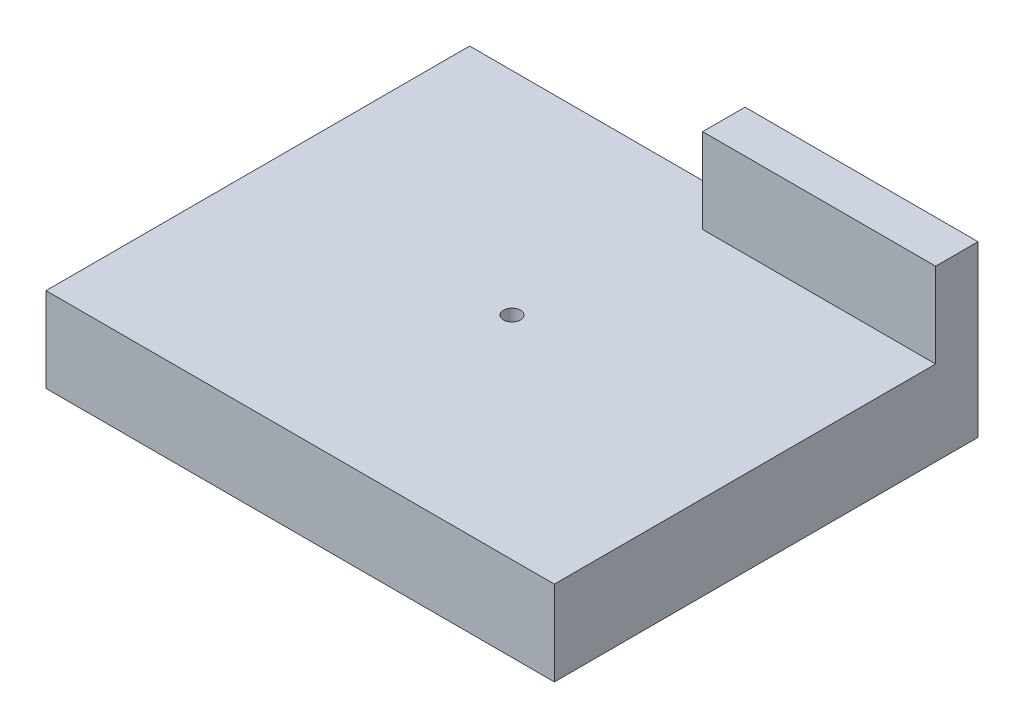
SolidWorks part; units mm, degrees
ref_plane "Front Plane" through (0, 0, 0) normal (0, 0, 1) x (1, 0, 0)
ref_plane "Top Plane" through (0, 0, 0) normal (0, 1, 0) x (1, 0, 0)
ref_plane "Right Plane" through (0, 0, 0) normal (1, 0, 0) x (0, 0, -1)
sketch "Sketch1" plane through (0, 0, 0) normal (0, 1, 0) x (1, 0, 0)
  line L1 (-30, -25) -> (30, -25)
  line L2 (-30, -25) -> (-30, 25)
  line L3 (-30, 25) -> (30, 25)
  line L4 (30, -25) -> (30, 25)
  line L5 (-30, -25) -> (30, 25) construction
  line L6 (-30, 25) -> (30, -25) construction
  point P0 (0, 0)
  dimension "D1" = 50
  dimension "D2" = 60
extrude "Boss-Extrude1" add sketch "Sketch1" along normal blind 20
sketch "Sketch2" plane through (0, 20, 0) normal (0, 1, 0) x (1, 0, 0)
  line L0 (-30, -25) -> (30, -25) construction
  line L1 (-30, 25) -> (2.5, 25)
  line L2 (-30, 25) -> (-30, -25)
  line L3 (-30, -25) -> (2.5, -25)
  line L4 (2.5, 25) -> (2.5, 20)
  line L6 (2.5, 20) -> (30, 20)
  line L8 (2.5, -25) -> (30, -25)
  line L9 (30, 20) -> (30, -25)
  dimension "D1" = 32.5
  dimension "D2" = 45
extrude "Cut-Extrude1" cut sketch "Sketch2" against normal blind 10
hole_wizard "2mm Diameter Hole" positions "Sketch4" profile "Sketch3" hole size "3/32" standard "ANSI Inch" end condition through all
sketch "Sketch4" plane through (0, 10, 0) normal (0, 1, 0) x (1, 0, 0)
  point P0 (0, 0)
sketch "Sketch3" plane through (0, 10, 0) normal (1, 0, 0) x (0, 0, 1)
  line L0 (0, 0) -> (0, 10)
  line L1 (0, 10) -> (1, 10)
  line L2 (1, 10) -> (1, 0)
  line L5 (1, 0) -> (0, 0)
  line L11 (0, -6.35) -> (0, 107.95) construction
  dimension "Thru Hole Dia." = 2
  dimension "Thru Hole Depth" = 10
